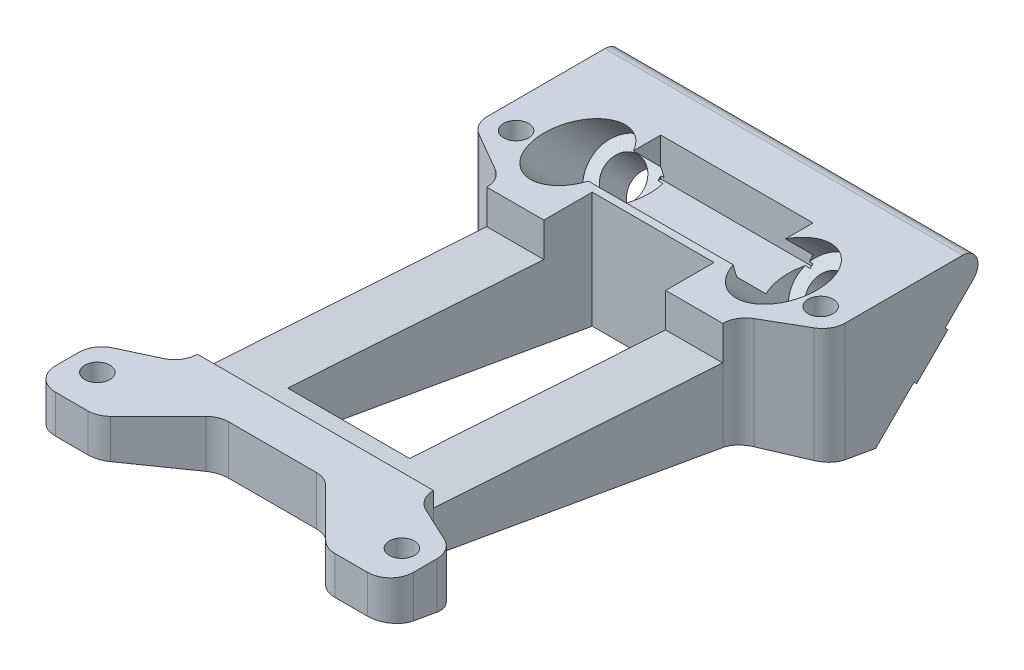
SolidWorks part; units mm, degrees
ref_plane "前视基准面" through (0, 0, 0) normal (0, 0, 1) x (1, 0, 0)
ref_plane "上视基准面" through (0, 0, 0) normal (0, 1, 0) x (1, 0, 0)
ref_plane "右视基准面" through (0, 0, 0) normal (1, 0, 0) x (0, 0, -1)
sketch "草图2" plane through (0, 0, 0) normal (0, 1, 0) x (1, 0, 0)
  line L0 (0, 0) -> (23.5, 0)
  line L1 (23.5, 0) -> (23.5, -19)
  line L4 (23.5, -80) -> (0, -80)
  line L5 (0, -80) -> (0, 0)
  line L6 (23.5, -19) -> (23.5, -80)
  dimension "D1" = 23.5
  dimension "D2" = 80
  dimension "D3" = 23.5
  dimension "D4" = 23.5
  dimension "D6" = 61
extrude "凸台-拉伸2" add sketch "草图2" along normal blind 5
mirror "镜向1" about plane through (0, 5, 80) normal (1, 0, 0) of "凸台-拉伸2"
sketch "草图5" plane through (0, 0, 0) normal (1, 0, 0) x (0, 0, -1)
  line L2 (-16.2635, -11.2635) -> (0, 5)
  line L7 (-7.1418, -2.1418) -> (-11.243, -6.243)
  line L8 (-7.1418, -2.1418) -> (-6.7882, -2.4953)
  line L9 (-11.243, -6.243) -> (-10.8894, -6.5966)
  line L10 (-6.7882, -2.4953) -> (-10.8894, -6.5966)
  line L11 (-8.8388, -4.5459) -> (-14.0224, 0.6377) construction
  line L12 (-80, 5) -> (0, 5) construction
  line L13 (-80, 0) -> (-16.2635, -11.2635)
  line L14 (-80, 0) -> (0, 0) construction
  line L15 (-80, 0) -> (0, 0)
  dimension "D1" = 23
  dimension "D2" = 10
  dimension "D3" = 45
  dimension "D5" = 5.8
  dimension "D6" = 0.5
extrude "凸台-拉伸3" add sketch "草图5" along normal mid plane 47
sketch "草图3" plane through (0, 5, 0) normal (0, 1, 0) x (1, 0, 0)
  line L0 (-41.875, -20) -> (42.0058, -20) construction
  line L1 (-48.5488, -75) -> (45.2773, -75) construction
  line L2 (-20, 7.7517) -> (-20, -80.1072) construction
  line L3 (20, 7.7517) -> (20, -77.5947) construction
  line L4 (-23.5, -80) -> (23.5, -80) construction
  circle A0 centre (-20, -20) radius 1.65
  circle A1 centre (20, -20) radius 1.65
  circle A2 centre (-20, -75) radius 1.65
  circle A3 centre (20, -75) radius 1.65
  point P10 (0, -80)
  dimension "D5" = 3.3
  dimension "D1" = 5
  dimension "D2" = 55
  dimension "D3" = 40
  dimension "D4" = 20
extrude "切除-拉伸1" cut sketch "草图3" against normal through all
sketch "草图8" plane through (0, 5, 0) normal (0, -1, 0) x (1, 0, 0)
  circle A0 centre (-20, 20) radius 3
  circle A1 centre (20, 20) radius 3
  circle A2 centre (20, 75) radius 3
  circle A3 centre (-20, 75) radius 3
  dimension "D1" = 6
extrude "切除-拉伸5" cut sketch "草图8" along normal up to next from offset 3 contours A0 | A1
sketch "草图12" plane through (0, 5, 0) normal (0, 1, 0) x (1, 0, 0)
  circle A1 centre (-20, -75) radius 3
  circle A2 centre (-20, -75) radius 3
  circle A3 centre (20, -75) radius 3
  circle A4 centre (20, -75) radius 3
  circle A5 centre (20, -20) radius 3
  circle A6 centre (20, -20) radius 3
  circle A7 centre (-20, -20) radius 3
  circle A8 centre (-20, -20) radius 3
  dimension "D1" = 0
  dimension "D2" = 0
  dimension "D3" = 0
  dimension "D4" = 0
extrude "切除-拉伸10" cut sketch "草图12" against normal up to next from offset 3 contours A2 | A4 offset against normal yes
sketch "草图4" plane through (0, 5, 0) normal (0, 1, 0) x (1, 0, 0)
  line L0 (-23.5, -80) -> (23.5, -80) construction
  line L1 (-10, -11) -> (10, -11)
  line L2 (-10, -11) -> (-10, -21)
  line L3 (-10, -21) -> (10, -21)
  line L4 (10, -11) -> (10, -21)
  line L5 (-15, -80) -> (-7, -72)
  line L6 (-7, -72) -> (7, -72)
  line L7 (7, -72) -> (15, -80)
  line L8 (15, -80) -> (-15, -80)
  line L9 (-23.5, -72) -> (-15.5, -68.2695)
  line L10 (-23.5, -80) -> (-23.5, 0) construction
  line L11 (-15.5, -68.2695) -> (-15.5, -26.6188)
  line L12 (-15.5, -26.6188) -> (-23.5, -22)
  line L13 (-23.5, -22) -> (-23.5, -72)
  line L14 (-23.5, -80) -> (23.5, -80) construction
  line L15 (23.5, 0) -> (-23.5, 0) construction
  line L16 (0, 0) -> (0, -5.79) construction
  line L17 (15.5, -26.6188) -> (23.5, -22)
  line L18 (15.5, -68.2695) -> (15.5, -26.6188)
  line L19 (23.5, -72) -> (15.5, -68.2695)
  line L20 (23.5, -22) -> (23.5, -72)
  line L21 (23.5, 0) -> (-23.5, 0) construction
  point P6 (0, -80)
  point P10 (0, -80)
  dimension "D2" = 10
  dimension "D3" = 20
  dimension "D4" = 10
  dimension "D5" = 30
  dimension "D6" = 8
  dimension "D7" = 45
  dimension "D8" = 45
  dimension "D9" = 8
  dimension "D10" = 22
  dimension "D11" = 8
  dimension "D12" = 65
  dimension "D13" = 60
  dimension "D14" = 11
extrude "切除-拉伸2" cut sketch "草图4" against normal blind 5 contours L4 L1 L2 L3
sketch "草图10" plane through (0, 5, 0) normal (0, 1, 0) x (1, 0, 0)
  line L1 (-8, -22) -> (8, -22)
  line L2 (-8, -22) -> (-8, -62)
  line L3 (-8, -62) -> (8, -62)
  line L4 (-7, -72) -> (-15, -80)
  line L5 (7, -72) -> (-7, -72)
  line L6 (15, -80) -> (7, -72)
  line L7 (-15, -80) -> (15, -80)
  line L8 (-7, -72) -> (-15, -80)
  line L9 (7, -72) -> (-7, -72)
  line L10 (15, -80) -> (7, -72)
  line L11 (-15, -80) -> (15, -80)
  line L12 (8, -22) -> (8, -62)
  line L20 (23.5, -22) -> (15.5, -26.6188)
  line L21 (23.5, -72) -> (23.5, -22)
  line L22 (15.5, -68.2695) -> (23.5, -72)
  line L23 (15.5, -26.6188) -> (15.5, -68.2695)
  line L24 (23.5, -22) -> (15.5, -26.6188)
  line L25 (23.5, -72) -> (23.5, -22)
  line L26 (15.5, -68.2695) -> (23.5, -72)
  line L27 (15.5, -26.6188) -> (15.5, -68.2695)
  line L28 (-15.5, -26.6188) -> (-23.5, -22)
  line L29 (-23.5, -22) -> (-23.5, -72)
  line L30 (-23.5, -72) -> (-15.5, -68.2695)
  line L31 (-15.5, -68.2695) -> (-15.5, -26.6188)
  line L32 (-15.5, -26.6188) -> (-23.5, -22)
  line L33 (-23.5, -22) -> (-23.5, -72)
  line L34 (-23.5, -72) -> (-15.5, -68.2695)
  line L35 (-15.5, -68.2695) -> (-15.5, -26.6188)
  point P2 (0, -80)
  dimension "D2" = 16
  dimension "D5" = 40
  dimension "D6" = 18
  dimension "D7" = 8
  dimension "D1" = 0
  dimension "D3" = 0
  dimension "D4" = 0
extrude "切除-拉伸11" cut sketch "草图10" against normal through all
fillet "圆角1" radius 3 14 edges at (-23.5, -2.6248, 22) (-23.5, 1.7931, 72) (23.5, 1.7931, 72) (23.5, -2.6248, 22) (15, 2.5, 80) (-15, 2.5, 80) (-15.5, -2.2167, 26.6188) (-15.5, 1.4635, 68.2695) (15.5, 1.4635, 68.2695) (15.5, -2.2167, 26.6188) (-7, 1.7931, 72) (7, 1.7931, 72) (-23.5, 2.5, 80) (23.5, 2.5, 80)
sketch "草图9" plane through (23.5, 0, 0) normal (1, 0, 0) x (0, 0, -1)
  line L0 (-5, 0) -> (0, 5)
  line L1 (-5, 0) -> (0, 0) construction
  line L2 (0, 5) -> (0, 0) construction
  line L3 (-5, 0) -> (0, 0)
  line L4 (0, 5) -> (0, 0)
extrude "切除-拉伸6" cut sketch "草图9" against normal through all
sketch "草图6" plane through (0, 2.1464, 2.1464) normal (0, -0.7071, -0.7071) x (1, 0, 0)
  line L0 (-23.5, 9.4645) -> (23.5, 9.4645) construction
  line L1 (-23.5, 6.5645) -> (-23.5, 12.3645) construction
  line L2 (23.5, 6.5645) -> (23.5, 12.3645) construction
  line L3 (-13.5, 12.3645) -> (-13.5, 6.5645) construction
  line L4 (23.5, 12.3645) -> (-23.5, 12.3645) construction
  line L5 (23.5, 6.5645) -> (-23.5, 6.5645) construction
  line L6 (13.5, 12.3645) -> (13.5, 6.5645) construction
  line L7 (23.5, 12.3645) -> (-23.5, 12.3645) construction
  line L8 (23.5, 6.5645) -> (-23.5, 6.5645) construction
  circle A0 centre (-13.5, 9.4645) radius 2.6
  circle A1 centre (13.5, 9.4645) radius 2.6
  dimension "D3" = 5.2
  dimension "D1" = 10
  dimension "D2" = 10
extrude "切除-拉伸3" cut sketch "草图6" against normal through all
sketch "草图7" plane through (0, 2.1464, 2.1464) normal (0, -0.7071, -0.7071) x (1, 0, 0)
  circle A0 centre (-13.5, 9.4645) radius 4.4
  circle A1 centre (13.5, 9.4645) radius 4.4
  dimension "D1" = 8.8
extrude "切除-拉伸4" cut sketch "草图7" against normal up to next from offset 5 offset against normal yes
fillet "圆角3" radius 2 1 edges at (0, 5, 0)
sketch "草图13" plane through (0, 5, 0) normal (0, 1, 0) x (1, 0, 0)
  line L1 (-15.5, -28.3509) -> (15.5, -28.3509)
  line L2 (-15.5, -28.3509) -> (-15.5, -66.3583)
  line L3 (-15.5, -66.3583) -> (15.5, -66.3583)
  line L4 (15.5, -28.3509) -> (15.5, -66.3583)
extrude "切除-拉伸12" [suppressed] cut sketch "草图13" against normal blind 2
sketch "草图14" plane through (-15.5, 0, 0) normal (-1, 0, 0) x (0, 0, 1)
  line L0 (28.3509, 5) -> (28.3509, 0.5)
  line L1 (28.3509, 5) -> (28.3509, -9.1274) construction
  line L2 (28.3509, 0.5) -> (66.3583, 3)
  line L3 (66.3583, -2.4107) -> (66.3583, 5) construction
  line L4 (66.3583, 3) -> (66.3583, 5)
  line L5 (66.3583, 5) -> (28.3509, 5)
  dimension "D1" = 4.5
  dimension "D2" = 2
extrude "切除-拉伸13" cut sketch "草图14" against normal through all
